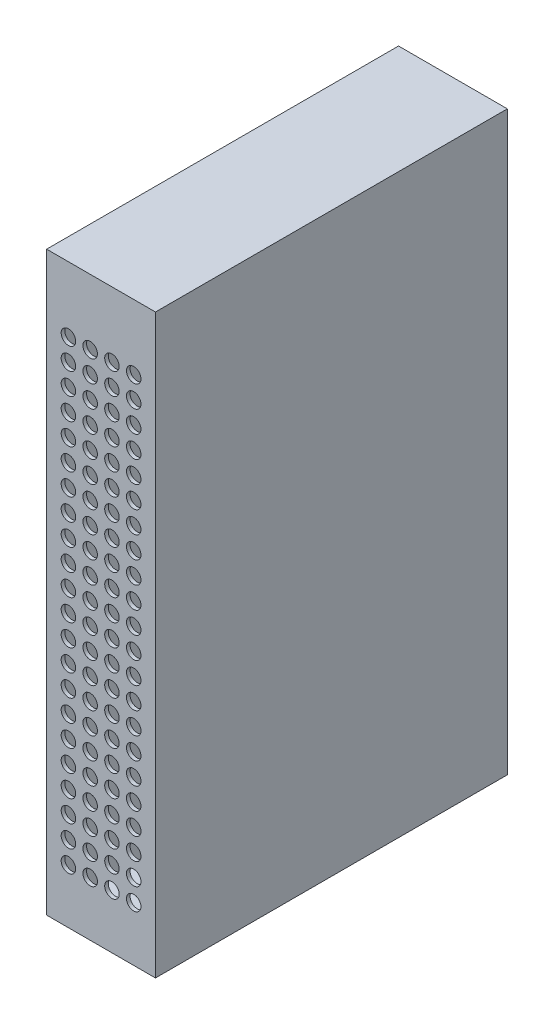
SolidWorks part; units mm, degrees
ref_plane "Front Plane" through (0, 0, 0) normal (0, 0, 1) x (1, 0, 0)
ref_plane "Top Plane" through (0, 0, 0) normal (0, 1, 0) x (1, 0, 0)
ref_plane "Right Plane" through (0, 0, 0) normal (1, 0, 0) x (0, 0, -1)
sketch "Sketch1" plane through (0, 0, 0) normal (0, 0, 1) x (1, 0, 0)
  line L1 (-15, 0) -> (15, 0)
  line L2 (-15, 0) -> (-15, 159)
  line L3 (-15, 159) -> (15, 159)
  line L4 (15, 0) -> (15, 159)
extrude "Case" add sketch "Sketch1" along normal blind 97
shell "Case_shell" thickness 1
ref_plane "Plane_z97" through (0, 0, 97) normal (0, 0, 1) x (1, 0, 0)
sketch "Sketch2" plane through (0, 0, 97) normal (0, 0, 1) x (1, 0, 0)
  circle A0 centre (-9, 15) radius 2
  circle A1 centre (-9, 21) radius 2
  circle A2 centre (-9, 27) radius 2
  circle A3 centre (-9, 33) radius 2
  circle A4 centre (-9, 39) radius 2
  circle A5 centre (-9, 45) radius 2
  circle A6 centre (-9, 51) radius 2
  circle A7 centre (-9, 57) radius 2
  circle A8 centre (-9, 63) radius 2
  circle A9 centre (-9, 69) radius 2
  circle A10 centre (-9, 75) radius 2
  circle A11 centre (-9, 81) radius 2
  circle A12 centre (-9, 87) radius 2
  circle A13 centre (-9, 93) radius 2
  circle A14 centre (-9, 99) radius 2
  circle A15 centre (-9, 105) radius 2
  circle A16 centre (-9, 111) radius 2
  circle A17 centre (-9, 117) radius 2
  circle A18 centre (-9, 123) radius 2
  circle A19 centre (-9, 129) radius 2
  circle A20 centre (-9, 135) radius 2
  circle A21 centre (-9, 141) radius 2
  circle A22 centre (-3, 15) radius 2
  circle A23 centre (-3, 21) radius 2
  circle A24 centre (-3, 27) radius 2
  circle A25 centre (-3, 33) radius 2
  circle A26 centre (-3, 39) radius 2
  circle A27 centre (-3, 45) radius 2
  circle A28 centre (-3, 51) radius 2
  circle A29 centre (-3, 57) radius 2
  circle A30 centre (-3, 63) radius 2
  circle A31 centre (-3, 69) radius 2
  circle A32 centre (-3, 75) radius 2
  circle A33 centre (-3, 81) radius 2
  circle A34 centre (-3, 87) radius 2
  circle A35 centre (-3, 93) radius 2
  circle A36 centre (-3, 99) radius 2
  circle A37 centre (-3, 105) radius 2
  circle A38 centre (-3, 111) radius 2
  circle A39 centre (-3, 117) radius 2
  circle A40 centre (-3, 123) radius 2
  circle A41 centre (-3, 129) radius 2
  circle A42 centre (-3, 135) radius 2
  circle A43 centre (-3, 141) radius 2
  circle A44 centre (3, 15) radius 2
  circle A45 centre (3, 21) radius 2
  circle A46 centre (3, 27) radius 2
  circle A47 centre (3, 33) radius 2
  circle A48 centre (3, 39) radius 2
  circle A49 centre (3, 45) radius 2
  circle A50 centre (3, 51) radius 2
  circle A51 centre (3, 57) radius 2
  circle A52 centre (3, 63) radius 2
  circle A53 centre (3, 69) radius 2
  circle A54 centre (3, 75) radius 2
  circle A55 centre (3, 81) radius 2
  circle A56 centre (3, 87) radius 2
  circle A57 centre (3, 93) radius 2
  circle A58 centre (3, 99) radius 2
  circle A59 centre (3, 105) radius 2
  circle A60 centre (3, 111) radius 2
  circle A61 centre (3, 117) radius 2
  circle A62 centre (3, 123) radius 2
  circle A63 centre (3, 129) radius 2
  circle A64 centre (3, 135) radius 2
  circle A65 centre (3, 141) radius 2
  circle A66 centre (9, 15) radius 2
  circle A67 centre (9, 21) radius 2
  circle A68 centre (9, 27) radius 2
  circle A69 centre (9, 33) radius 2
  circle A70 centre (9, 39) radius 2
  circle A71 centre (9, 45) radius 2
  circle A72 centre (9, 51) radius 2
  circle A73 centre (9, 57) radius 2
  circle A74 centre (9, 63) radius 2
  circle A75 centre (9, 69) radius 2
  circle A76 centre (9, 75) radius 2
  circle A77 centre (9, 81) radius 2
  circle A78 centre (9, 87) radius 2
  circle A79 centre (9, 93) radius 2
  circle A80 centre (9, 99) radius 2
  circle A81 centre (9, 105) radius 2
  circle A82 centre (9, 111) radius 2
  circle A83 centre (9, 117) radius 2
  circle A84 centre (9, 123) radius 2
  circle A85 centre (9, 129) radius 2
  circle A86 centre (9, 135) radius 2
  circle A87 centre (9, 141) radius 2
extrude "Perforation" cut sketch "Sketch2" against normal blind 1
